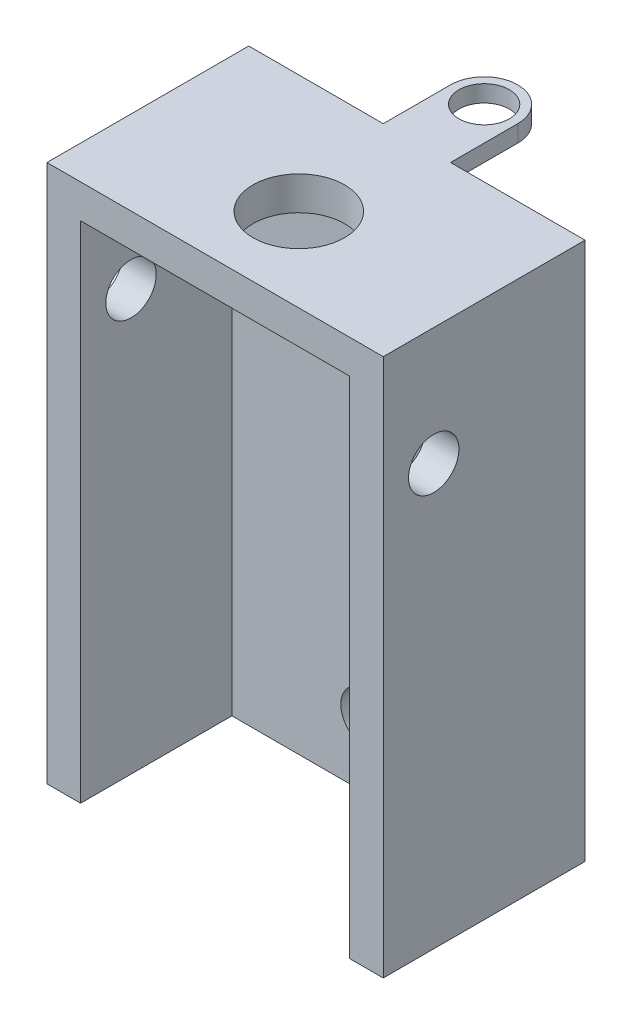
SolidWorks part; units mm, degrees
ref_plane "Plan de face" through (0, 0, 0) normal (0, 0, 1) x (1, 0, 0)
ref_plane "Plan de dessus" through (0, 0, 0) normal (0, 1, 0) x (1, 0, 0)
ref_plane "Plan de droite" through (0, 0, 0) normal (1, 0, 0) x (0, 0, -1)
sketch "Esquisse1" plane through (0, 0, 0) normal (0, 0, 1) x (1, 0, 0)
  line L1 (-10, 16) -> (10, 16)
  line L2 (-10, 16) -> (-10, -16)
  line L3 (-10, -16) -> (10, -16)
  line L4 (10, 16) -> (10, -16)
  line L5 (-10, 16) -> (10, -16) construction
  line L6 (-10, -16) -> (10, 16) construction
  circle A0 centre (0, -12.1626) radius 1.524 construction
  circle A1 centre (0, -12.1626) radius 1.524
  point P0 (0, 0)
  dimension "D1" = 20
  dimension "D2" = 32
extrude "Boss.-Extru.1" add sketch "Esquisse1" along normal blind 3
sketch "Esquisse2" plane through (0, 0, 0) normal (0, 0, 1) x (1, 0, 0)
  line L8 (-10, -16) -> (10, -16) construction
  line L9 (8, -16) -> (10, -16)
  line L12 (8, -14) -> (8, 14)
  line L13 (8, 14) -> (-8, 14)
  line L14 (-8, 14) -> (-8, -14)
  line L15 (-8, -14) -> (8, -14)
  line L16 (8, -16) -> (8, 14)
  line L17 (8, 14) -> (-8, 14)
  line L18 (-8, 14) -> (-8, -16)
  line L20 (10, -16) -> (10, 16)
  line L21 (10, 16) -> (-10, 16)
  line L22 (-10, 16) -> (-10, -16)
  line L23 (-10, -16) -> (10, -16)
  line L24 (10, -16) -> (10, 16)
  line L25 (10, 16) -> (-10, 16)
  line L26 (-10, 16) -> (-10, -16)
  line L27 (-10, -16) -> (-8, -16)
  point P2 (-8, -15)
  point P12 (8, -15)
  dimension "D1" = 2
  dimension "D2" = 0
extrude "Boss.-Extru.2" add sketch "Esquisse2" along normal blind 12
sketch "Esquisse3" plane through (0, 0, 0) normal (0, 1, 0) x (1, 0, 0)
  circle A1 centre (0, -7.024) radius 2.725 construction
  circle A2 centre (0, -7.024) radius 2.725
extrude "Enlèv. mat.-Extru.1" cut sketch "Esquisse3" against normal through all both and the other way through all
sketch "Esquisse4" plane through (0, 0, 0) normal (1, 0, 0) x (0, 0, -1)
  line L0 (-12, -16) -> (-12, 16) construction
  line L1 (-12, 16) -> (0, 16) construction
  circle A0 centre (-9, 9) radius 1.5
  dimension "D1" = 3
  dimension "D2" = 3
  dimension "D3" = 7
extrude "Enlèv. mat.-Extru.2" cut sketch "Esquisse4" against normal through all both and the other way through all
sketch "Esquisse5" plane through (0, 16, 0) normal (0, 1, 0) x (1, 0, 0)
  line L0 (-2, 0) -> (-2, 4)
  line L1 (10, 0) -> (-10, 0) construction
  line L2 (2, 4) -> (2, 0)
  line L3 (2, 0) -> (-2, 0)
  arc A0 (-2, 4) -> (2, 4) centre (0, 4) cw
  circle A1 centre (0, 4) radius 1.5
  dimension "D1" = 2
  dimension "D2" = 3
  dimension "D3" = 4
extrude "Boss.-Extru.3" add sketch "Esquisse5" against normal blind 1
